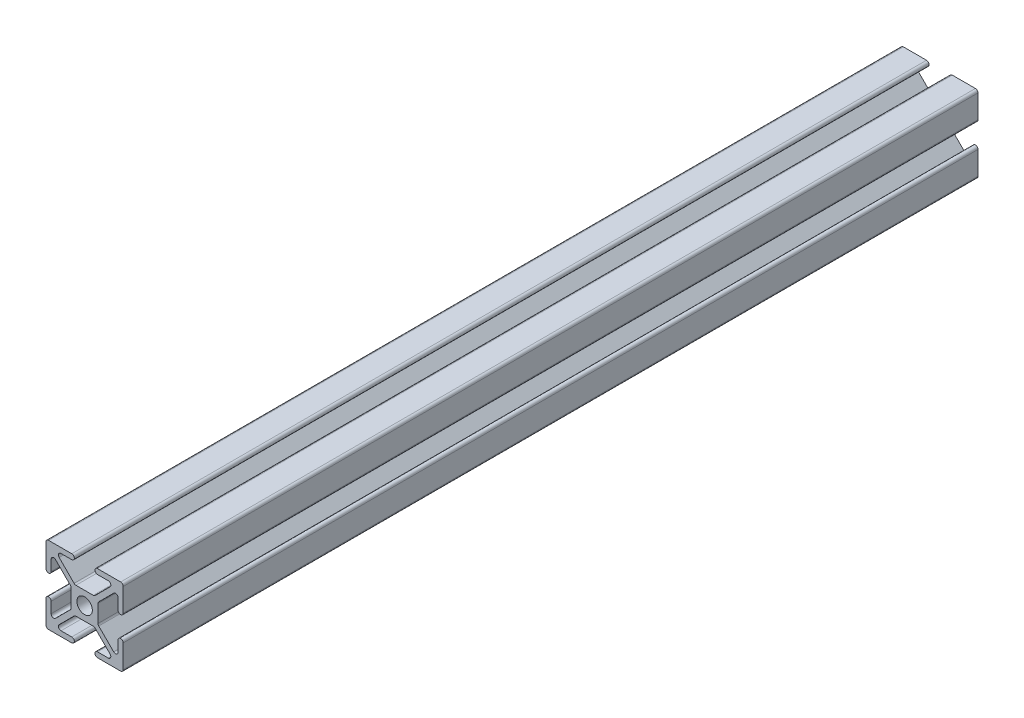
SolidWorks part; units mm, degrees
ref_plane "Alzado" through (0, 0, 0) normal (0, 0, 1) x (1, 0, 0)
ref_plane "Planta" through (0, 0, 0) normal (0, 1, 0) x (1, 0, 0)
ref_plane "Vista lateral" through (0, 0, 0) normal (1, 0, 0) x (0, 0, -1)
sketch "Croquis1" plane through (0, 0, 0) normal (0, 0, 1) x (1, 0, 0)
  line L1 (-14, 15) -> (14, 15)
  line L2 (-15, 14) -> (-15, -14)
  line L3 (-14, -15) -> (14, -15)
  line L4 (15, 14) -> (15, -14)
  line L5 (-15, 15) -> (15, -15) construction
  line L6 (-15, -15) -> (15, 15) construction
  arc A0 (-14, 15) -> (-15, 14) centre (-14, 14) ccw
  arc A1 (14, -15) -> (15, -14) centre (14, -14) ccw
  arc A2 (-14, -15) -> (-15, -14) centre (-14, -14) cw
  arc A3 (15, 14) -> (14, 15) centre (14, 14) ccw
  point P0 (0, 0)
  dimension "D3" = 1
  dimension "D4" = 1
  dimension "D1" = 30
  dimension "D2" = 30
extrude "Saliente-Extruir1" add sketch "Croquis1" against normal blind 332
sketch "Croquis2" plane through (0, 0, 0) normal (0, 0, 1) x (1, 0, 0)
  circle A0 centre (0, 0) radius 3
  dimension "D1" = 6
sketch "Croquis3" plane through (0, 0, 0) normal (0, 0, 1) x (1, 0, 0)
  line L0 (-15, 0) -> (15, 0) construction
  line L1 (4.0787, -5.4929) -> (9.8787, -11.2929)
  line L2 (-11.2929, 9.8787) -> (-5.4929, 4.0787)
  line L3 (-9.8787, 11.2929) -> (-4.0787, 5.4929)
  line L4 (-13, 9.1716) -> (-13, 5)
  line L5 (-15, 14) -> (-15, -14) construction
  line L6 (-5.2, 3.3716) -> (-5.2, -3.3716)
  line L7 (-9.1716, 13) -> (-5, 13)
  line L8 (9.8787, 11.2929) -> (4.0787, 5.4929)
  line L9 (11.2929, 9.8787) -> (5.4929, 4.0787)
  line L10 (-3.3716, 5.2) -> (3.3716, 5.2)
  line L11 (14, 15) -> (-14, 15) construction
  line L12 (13, 9.1716) -> (13, 5)
  line L13 (5.2, 3.3716) -> (5.2, -3.3716)
  line L14 (15, -14) -> (15, 14) construction
  line L15 (-9.1716, -13) -> (-5, -13)
  line L16 (-3.3716, -5.2) -> (3.3716, -5.2)
  line L17 (-14, -15) -> (14, -15) construction
  line L18 (-5.4929, -4.0787) -> (-11.2929, -9.8787)
  line L19 (5.4929, -4.0787) -> (11.2929, -9.8787)
  line L20 (-4.0787, -5.4929) -> (-9.8787, -11.2929)
  line L21 (5, -13) -> (9.1716, -13)
  line L22 (-13, -5) -> (-13, -9.1716)
  line L23 (13, -5) -> (13, -9.1716)
  line L24 (0, 15) -> (0, -5.2) construction
  line L34 (5, 13) -> (9.1716, 13)
  arc A0 (9.8787, 11.2929) -> (9.1716, 13) centre (9.1716, 12) ccw
  arc A1 (-9.8787, 11.2929) -> (-9.1716, 13) centre (-9.1716, 12) cw
  arc A2 (9.8787, 11.2929) -> (9.1716, 13) centre (9.1716, 12) ccw
  arc A3 (13, 9.1716) -> (11.2929, 9.8787) centre (12, 9.1716) ccw
  arc A4 (11.2929, -9.8787) -> (13, -9.1716) centre (12, -9.1716) ccw
  arc A5 (9.1716, -13) -> (9.8787, -11.2929) centre (9.1716, -12) ccw
  arc A6 (-9.1716, -13) -> (-9.8787, -11.2929) centre (-9.1716, -12) cw
  arc A7 (-11.2929, -9.8787) -> (-13, -9.1716) centre (-12, -9.1716) cw
  arc A8 (-13, 9.1716) -> (-11.2929, 9.8787) centre (-12, 9.1716) cw
  arc A9 (-4.0787, -5.4929) -> (-3.3716, -5.2) centre (-3.3716, -6.2) cw
  arc A10 (3.3716, -5.2) -> (4.0787, -5.4929) centre (3.3716, -6.2) cw
  arc A11 (5.4929, -4.0787) -> (5.2, -3.3716) centre (6.2, -3.3716) cw
  arc A12 (5.2, 3.3716) -> (5.4929, 4.0787) centre (6.2, 3.3716) cw
  arc A13 (3.3716, 5.2) -> (4.0787, 5.4929) centre (3.3716, 6.2) ccw
  arc A14 (-3.3716, 5.2) -> (-4.0787, 5.4929) centre (-3.3716, 6.2) cw
  arc A15 (-5.4929, -4.0787) -> (-5.2, -3.3716) centre (-6.2, -3.3716) ccw
  arc A16 (-5.2, 3.3716) -> (-5.4929, 4.0787) centre (-6.2, 3.3716) ccw
  circle A17 centre (-14, -5) radius 1
  circle A18 centre (-14, 5) radius 1
  circle A19 centre (-5, -14) radius 1
  circle A20 centre (5, -14) radius 1
  circle A21 centre (14, 5) radius 1
  circle A22 centre (14, -5) radius 1
  circle A23 centre (-5, 14) radius 1
  circle A24 centre (5, 14) radius 1
  point P20 (-11.5858, -13)
  point P30 (-13, -11.5858)
  point P43 (-3.7858, -5.2)
  point P50 (3.7858, -5.2)
  point P53 (5.2, -3.7858)
  point P62 (-5.2, -3.7858)
  line M2 (-15, 14) -> (-15, -14)
  line M4 (-14, -15) -> (14, -15)
  line M6 (15, -14) -> (15, 14)
  line M8 (14, 15) -> (-14, 15)
  dimension "D6" = 9.8
  dimension "D7" = 2
  dimension "D12" = 2
  dimension "D19" = 1
  dimension "D2" = 1
  dimension "D3" = 1
  dimension "D4" = 1
  dimension "D16" = 1
  dimension "D5" = 2
  dimension "D8" = 9.8
  dimension "D9" = 2
  dimension "D10" = 9.8
  dimension "D11" = 9.8
  dimension "D15" = 1
  dimension "D20" = 1
  dimension "D23" = 1
  dimension "D24" = 1
  dimension "D27" = 1
  dimension "D28" = 1
extrude "Cortar-Extruir1" cut sketch "Croquis2" against normal through all
extrude "Cortar-Extruir3" cut sketch "Croquis3" against normal through all contours A18 A17 L22 A7 L18 A15 L6 A16 L2 A8 L4 M2 | A24 A23 L7 A1 L3 A14 L10 A13 L8 A0 L34 M8 | A20 L21 A5 L1 A10 L16 A9 L20 A6 L15 A19 M4 | A22 A21 L12 A3 L9 A12 L13 A11 L19 A4 L23 M6
